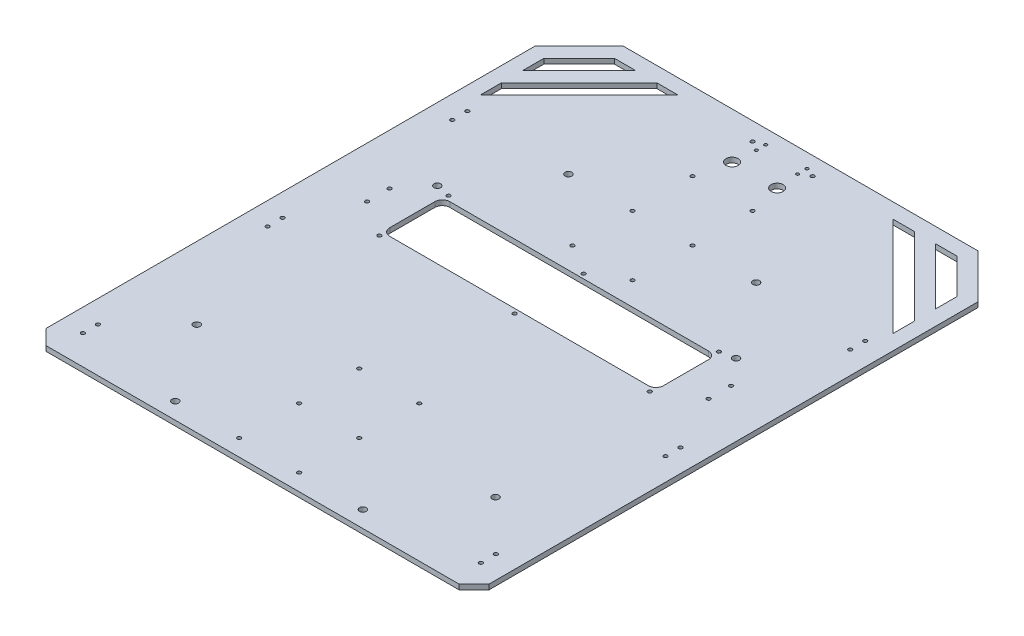
SolidWorks part; units mm, degrees
material "1060 Alloy"
ref_plane "Front Plane" through (0, 0, 0) normal (0, 0, 1) x (1, 0, 0)
ref_plane "Top Plane" through (0, 0, 0) normal (0, 1, 0) x (1, 0, 0)
ref_plane "Right Plane" through (0, 0, 0) normal (1, 0, 0) x (0, 0, -1)
sketch "Sketch2" plane through (0, 0, 0) normal (0, 1, 0) x (1, 0, 0)
  line L0 (295, -345.201) -> (275.201, -365)
  line L1 (-295, -365) -> (295, -365)
  line L2 (-295, -365) -> (-295, 365)
  line L3 (-295, 365) -> (295, 365)
  line L4 (295, -365) -> (295, 365)
  line L5 (-295, -365) -> (295, 365) construction
  line L6 (-295, 365) -> (295, -365) construction
  line L7 (0, 558.5624) -> (0, -892.0297) construction
  line L8 (236.3101, 365) -> (295, 306.3101)
  line L9 (228.0259, 345) -> (199.7416, 345)
  line L10 (-172.2875, -10) -> (172.2875, -10)
  line L11 (-182.2875, 0) -> (-182.2875, 60)
  line L12 (-172.2875, 70) -> (172.2875, 70)
  line L13 (182.2875, 0) -> (182.2875, 60)
  line L14 (-182.2875, -10) -> (182.2875, 70) construction
  line L15 (-182.2875, 70) -> (182.2875, -10) construction
  line L16 (199.7416, 345) -> (275, 269.7416)
  line L17 (275, 269.7416) -> (275, 298.0259)
  line L18 (275, 298.0259) -> (228.0259, 345)
  line L19 (171.4573, 345) -> (275, 241.4573)
  line L20 (275, 241.4573) -> (275, 213.1731)
  line L21 (275, 213.1731) -> (143.1731, 345)
  line L22 (143.1731, 345) -> (171.4573, 345)
  line L23 (-295, -345.201) -> (-275.201, -365)
  line L24 (-236.3101, 365) -> (-295, 306.3101)
  line L25 (-275, 298.0259) -> (-228.0259, 345)
  line L26 (-275, 269.7416) -> (-275, 298.0259)
  line L27 (-199.7416, 345) -> (-275, 269.7416)
  line L28 (-228.0259, 345) -> (-199.7416, 345)
  line L29 (-275, 213.1731) -> (-143.1731, 345)
  line L30 (-275, 241.4573) -> (-275, 213.1731)
  line L31 (-171.4573, 345) -> (-275, 241.4573)
  line L32 (-143.1731, 345) -> (-171.4573, 345)
  circle A0 centre (265, -306) radius 2.5
  circle A1 centre (265, -326) radius 2.5
  circle A2 centre (265, -60) radius 2.5
  circle A3 centre (265, -80) radius 2.5
  circle A4 centre (265, 186) radius 2.5
  circle A5 centre (265, 166) radius 2.5
  circle A6 centre (125, -343) radius 4.5
  circle A7 centre (40, -343) radius 2.5
  circle A8 centre (40, -263) radius 2.5
  circle A9 centre (40, -183) radius 2.5
  circle A10 centre (0, -16) radius 2.5
  circle A11 centre (0, 76) radius 2.5
  circle A12 centre (40, 101) radius 2.5
  circle A13 centre (40, 181) radius 2.5
  circle A14 centre (40, 261) radius 2.5
  circle A15 centre (180, -16) radius 2.5
  circle A16 centre (180, 76) radius 2.5
  circle A17 centre (227.5312, 45) radius 2.5
  circle A18 centre (227.5313, 15) radius 2.5
  circle A19 centre (199, -240.3812) radius 4.5
  circle A20 centre (199, 80) radius 4.5
  circle A21 centre (125, 180.7031) radius 4.5
  arc A22 (172.2875, -10) -> (182.2875, 0) centre (172.2875, 0) ccw
  arc A23 (172.2875, 70) -> (182.2875, 60) centre (172.2875, 60) cw
  arc A24 (-172.2875, -10) -> (-182.2875, 0) centre (-172.2875, 0) cw
  arc A25 (-182.2875, 60) -> (-172.2875, 70) centre (-172.2875, 60) cw
  circle A26 centre (40, 341) radius 2.5
  circle A27 centre (30, 303.7344) radius 8
  circle A28 centre (27.5, 346) radius 2
  circle A29 centre (27.5, 333.5) radius 2
  circle A30 centre (-27.5, 333.5) radius 2
  circle A31 centre (-40, 341) radius 2.5
  circle A32 centre (-27.5, 346) radius 2
  circle A33 centre (-30, 303.7344) radius 8
  circle A34 centre (-40, 261) radius 2.5
  circle A35 centre (-40, 181) radius 2.5
  circle A36 centre (-40, 101) radius 2.5
  circle A37 centre (-125, 180.7031) radius 4.5
  circle A38 centre (-265, 186) radius 2.5
  circle A39 centre (-265, 166) radius 2.5
  circle A40 centre (-199, 80) radius 4.5
  circle A41 centre (-180, 76) radius 2.5
  circle A42 centre (-227.5313, 15) radius 2.5
  circle A43 centre (-227.5312, 45) radius 2.5
  circle A44 centre (-180, -16) radius 2.5
  circle A45 centre (-265, -80) radius 2.5
  circle A46 centre (-265, -60) radius 2.5
  circle A47 centre (-40, -183) radius 2.5
  circle A48 centre (-40, -263) radius 2.5
  circle A49 centre (-199, -240.3812) radius 4.5
  circle A50 centre (-265, -326) radius 2.5
  circle A51 centre (-265, -306) radius 2.5
  circle A52 centre (-125, -343) radius 4.5
  circle A53 centre (-40, -343) radius 2.5
  point P0 (0, 0)
  point P33 (0, 30)
  point P48 (0, -365)
  dimension "D9" = 5
  dimension "D15" = 9
  dimension "D18" = 5
  dimension "D25" = 5
  dimension "D34" = 124.6188
  dimension "D44" = 10
  dimension "D47" = 16
  dimension "D49" = 4
  dimension "D1" = 590
  dimension "D2" = 730
  dimension "D3" = 45
  dimension "D4" = 28
  dimension "D5" = 45
  dimension "D6" = 83
  dimension "D7" = 265
  dimension "D8" = 20
  dimension "D10" = 39
  dimension "D11" = 20
  dimension "D12" = 20
  dimension "D13" = 285
  dimension "D14" = 531
  dimension "D16" = 22
  dimension "D17" = 170
  dimension "255" = 255
  dimension "D19" = 80
  dimension "D20" = 80
  dimension "D21" = 355
  dimension "D22" = 435
  dimension "D23" = 112.7125
  dimension "D24" = 349
  dimension "D26" = 441
  dimension "D27" = 466
  dimension "D28" = 80
  dimension "D29" = 80
  dimension "D30" = 115
  dimension "D31" = 67.4688
  dimension "D32" = 380
  dimension "D33" = 30
  dimension "D35" = 96
  dimension "D36" = 445
  dimension "D37" = 545.7031
  dimension "D38" = 20
  dimension "D39" = 20
  dimension "D40" = 20
  dimension "D41" = 20
  dimension "D42" = 20
  dimension "D43" = 20
  dimension "D45" = 80
  dimension "D46" = 668.7344
  dimension "D48" = 30
  dimension "D50" = 27.5
  dimension "D51" = 12.5
  dimension "D52" = 698.5
extrude "Boss-Extrude1" add sketch "Sketch2" along normal blind 6.7 contours L3 L24 L2 L23 L1 L0 L4 L8 A52 A50 A48 A46 A44 A42 A40 A38 A36 A34 A32 A30 A29 A28 A27 A26 A21 A20 A19 A18 A17
